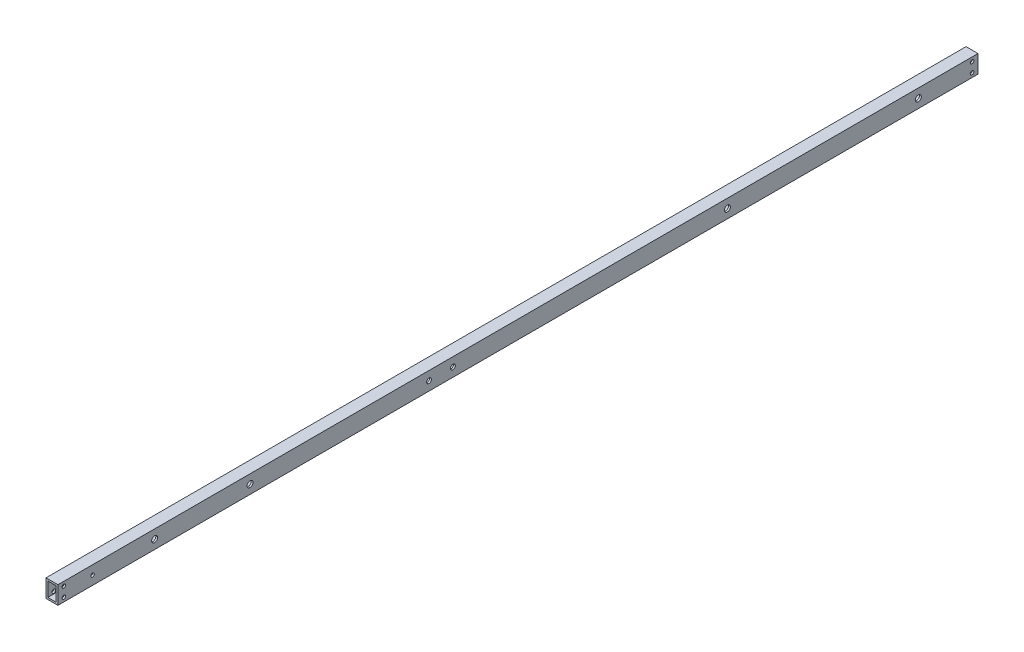
SolidWorks part; units mm, degrees
ref_plane "正面" through (0, 0, 0) normal (0, 0, 1) x (1, 0, 0)
ref_plane "平面" through (0, 0, 0) normal (0, 1, 0) x (1, 0, 0)
ref_plane "右側面" through (0, 0, 0) normal (1, 0, 0) x (0, 0, -1)
sketch "ｽｹｯﾁ1" plane through (0, 0, 0) normal (0, 0, 1) x (1, 0, 0)
  line L1 (-5, -7.5) -> (5, -7.5)
  line L2 (-5, -7.5) -> (-5, 7.5)
  line L3 (-5, 7.5) -> (5, 7.5)
  line L4 (5, -7.5) -> (5, 7.5)
  line L5 (-5, -7.5) -> (5, 7.5) construction
  line L6 (-5, 7.5) -> (5, -7.5) construction
  point P0 (0, 0)
  dimension "D1" = 15
  dimension "D2" = 10
extrude "押し出し-薄板1" add sketch "ｽｹｯﾁ1" along normal blind 771 thin thin type one direction reverse wall 1.5
sketch "ｽｹｯﾁ2" plane through (5, 0, 0) normal (1, 0, 0) x (0, 0, -1)
  line L0 (-539, 0) -> (49461, 0) construction
  line L1 (-771, -7.5) -> (-771, 7.5) construction
  line L2 (0, -7.5) -> (0, 7.5) construction
  line L4 (-450, 7.5) -> (-450, -7.5) construction
  line L5 (-771, 7.5) -> (0, 7.5) construction
  line L6 (-771, -7.5) -> (0, -7.5) construction
  circle A1 centre (-5, 4) radius 1.5
  circle A2 centre (-5, -4) radius 1.5
  circle A3 centre (-766, 4) radius 1.5
  circle A4 centre (-766, -4) radius 1.5
  circle A5 centre (-50, 0) radius 2.5
  circle A6 centre (-742, 0) radius 1.5
  circle A7 centre (-690, 0) radius 2.5
  circle A8 centre (-440, 0) radius 2
  circle A9 centre (-460, 0) radius 2
  circle A10 centre (-610, 0) radius 2.5
  circle A15 centre (-210, 0) radius 2.5
  point P4 (-771, 0)
  dimension "D1" = 3
  dimension "D2" = 8
  dimension "D3" = 8
  dimension "D4" = 5
  dimension "D5" = 3
  dimension "D6" = 5
  dimension "D7" = 50
  dimension "D8" = 5
  dimension "D9" = 29
  dimension "D10" = 3
  dimension "D12" = 81
  dimension "D14" = 20
  dimension "D15" = 4
  dimension "D16" = 5
  dimension "D17" = 80
  dimension "D21" = 160
  dimension "D11" = 0
  dimension "D13" = 450
extrude "ｶｯﾄ - 押し出し1" cut sketch "ｽｹｯﾁ2" against normal through all
sketch "ｽｹｯﾁ3" plane through (-5, 0, 0) normal (-1, 0, 0) x (0, 0, 1)
  circle A0 centre (440, 0) radius 4
  circle A1 centre (460, 0) radius 4
  dimension "D1" = 8
extrude "ｶｯﾄ - 押し出し2" cut sketch "ｽｹｯﾁ3" against normal up to surface (1.5 mm away) up to face at (-3.5, 0, 458)
